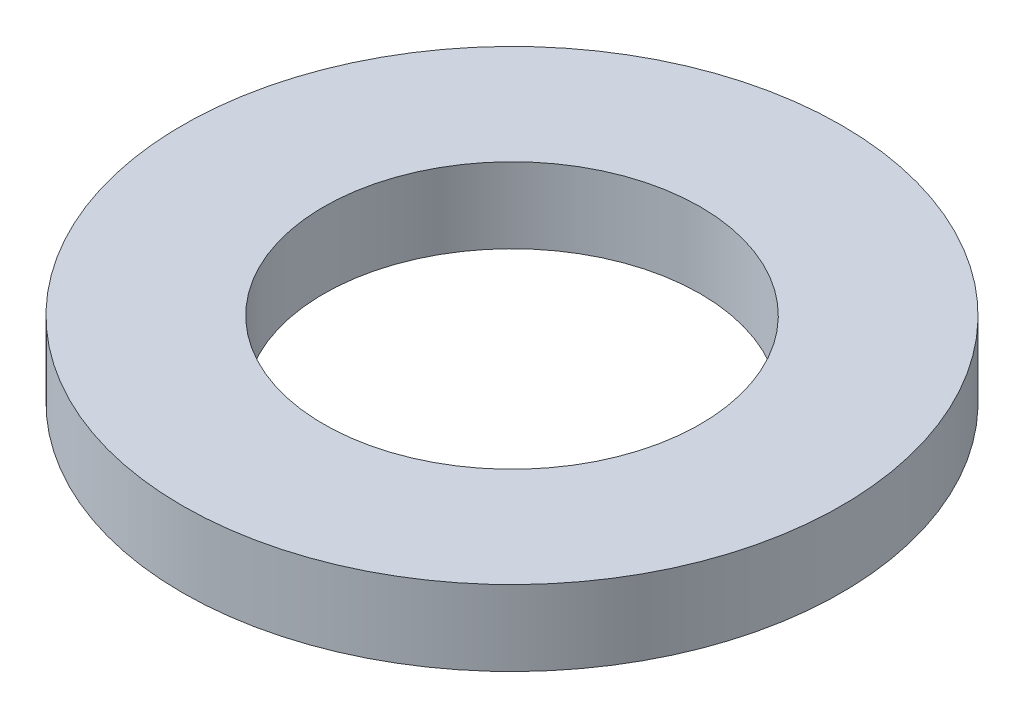
SolidWorks part; units mm, degrees
ref_plane "Front Plane" through (0, 0, 0) normal (0, 0, 1) x (1, 0, 0)
ref_plane "Top Plane" through (0, 0, 0) normal (0, 1, 0) x (1, 0, 0)
ref_plane "Right Plane" through (0, 0, 0) normal (1, 0, 0) x (0, 0, -1)
sketch "Sketch1" plane through (0, 0, 0) normal (0, 0, 1) x (1, 0, 0)
  line L0 (7, 0) -> (7, 1.6)
  line L1 (7, 1.6) -> (4, 1.6)
  line L2 (4, 1.6) -> (4, 0)
  line L3 (4, 0) -> (7, 0)
  line L4 (0, 1.6) -> (0, 0) construction
revolve "Revolve1" add sketch "Sketch1" angle 360 about L4
